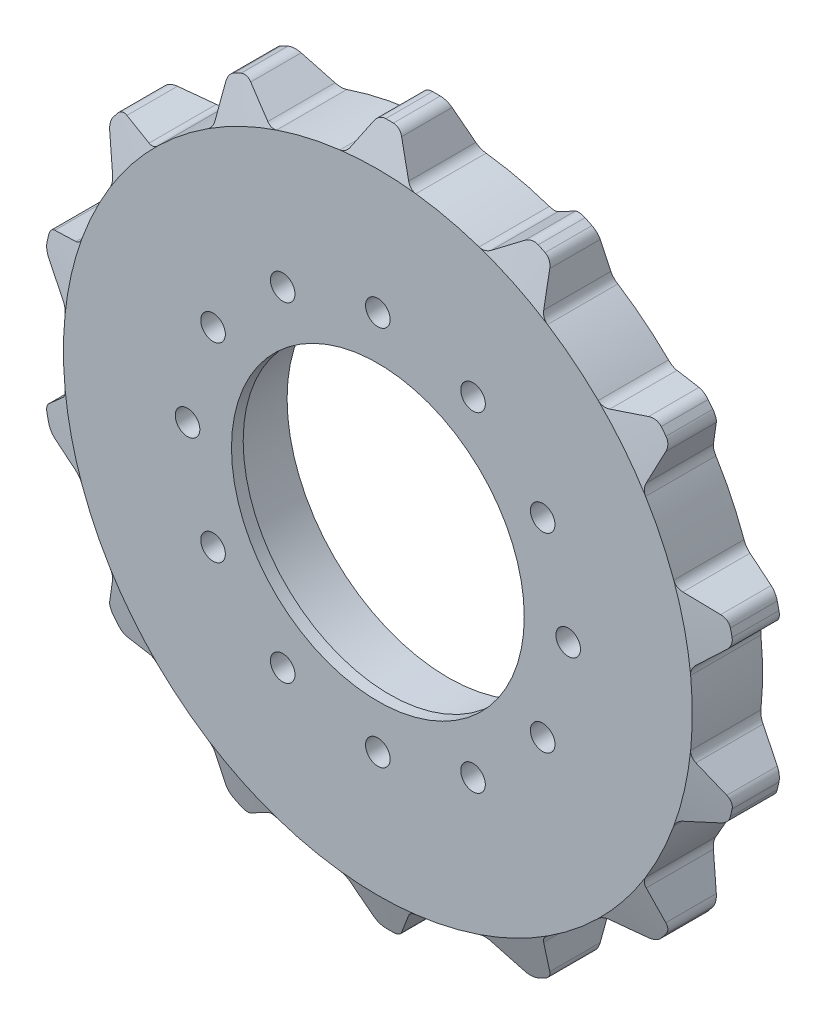
SolidWorks part; units mm, degrees
material "ABS"
ref_plane "Front" through (0, 0, 0) normal (0, 0, 1) x (1, 0, 0)
ref_plane "Top" through (0, 0, 0) normal (0, 1, 0) x (1, 0, 0)
ref_plane "Right" through (0, 0, 0) normal (1, 0, 0) x (0, 0, -1)
ref_axis "CL" through (0, 0, -5.5) along (0, 0, 1)
sketch "Sketch1" plane through (0, 0, 0) normal (0, 0, 1) x (1, 0, 0)
  circle A0 centre (0, 0) radius 53.7
  dimension "D1" = 107.4
extrude "Main Body" add sketch "Sketch1" along normal mid plane 12
sketch "Sketch2" plane through (0, 0, -6) normal (0, 0, -1) x (-1, 0, 0)
  line L0 (5.5, -53.4176) -> (1.8019, -59.8229)
  line L2 (-1.8019, -59.8229) -> (-5.5, -53.4176)
  line L3 (0, -59.85) -> (0, -53.7) construction
  circle A0 centre (0, 0) radius 53.7 construction
  arc A1 (5.5, -53.4176) -> (-5.5, -53.4176) centre (0, 0) cw
  arc A3 (1.8019, -59.8229) -> (-1.8019, -59.8229) centre (0, 0) cw
  point P10 (0, -53.7)
  circle M6 centre (0, 0) radius 53.7
  dimension "D1" = 11
  dimension "D2" = 60
  dimension "D3" = 59.85
extrude "Track Tooth" add sketch "Sketch2" against normal up to surface (12 mm away) contours L3 A3 L0 A1 | A3 L3 L2 M6 up to face at (53.7, 0, 6)
fillet "Fillet5" radius 2 4 edges at (5.5, -53.4176, 0) (-5.5, -53.4176, 0) (1.8019, -59.8229, 0) (-1.8019, -59.8229, 0)
pattern_circular "CirPattern4" count 14 over 360 about axis through (0, 0, 0) along (0, 0, 1) of "Track Tooth", "Fillet5"
sketch "Sketch3" plane through (0, 0, 0) normal (1, 0, 0) x (0, 0, -1)
  line L0 (-6, -59.85) -> (-4, -59.85)
  line L1 (-4, -59.85) -> (-6, -53.7)
  line L2 (-6, -53.7) -> (-6, -59.85)
  line L3 (-6, -50.8418) -> (-6, -53.3069) construction
  line L4 (-6, -53.4176) -> (-6, -53.7) construction
  line L5 (6, -58.8465) -> (6, -54.2923) construction
  line L8 (0, 0) -> (0, -59.85) construction
  line L9 (-6, -59.85) -> (6, -59.85) construction
  line L10 (4, -59.85) -> (6, -59.85)
  line L11 (6, -59.85) -> (6, -53.7)
  line L12 (6, -53.7) -> (4, -59.85)
  dimension "D1" = 2
  dimension "D2" = 53.7
revolve "Cut-Revolve3" cut sketch "Sketch3" angle 360 about axis through (0, 0, -5.5) along (0, 0, 1)
sketch "Sketch5" plane through (0, 0, -6) normal (0, 0, -1) x (-1, 0, 0)
  circle A0 centre (0, 0) radius 27.5
  dimension "D1" = 55
extrude "Cut-Extrude1" cut sketch "Sketch5" against normal blind 10 and the other way through all
hole_wizard "M5x0.8 Tapped Hole1" positions "Sketch7" profile "Sketch8" tap size "M5x0.8" standard "ANSI Metric" end condition up to next
sketch "Sketch7" plane through (0, 0, 6) normal (0, 0, -1) x (-1, 0, 0)
  line L0 (0, 0) -> (32.5, 0) construction
  circle A0 centre (0, 0) radius 32.5 construction
  point P0 (32.5, 0)
  dimension "D1" = 65
sketch "Sketch8" plane through (-32.5, 0, 6) normal (1, 0, 0) x (0, -1, 0)
  line L0 (0, 0) -> (0, 12.001)
  line L1 (0, 12.001) -> (2.1, 12.001)
  line L2 (2.1, 12.001) -> (2.1, 0)
  line L5 (2.1, 0) -> (0, 0)
  line L11 (0, -6.35) -> (0, 107.95) construction
  dimension "Thread Major Dia." = 4.2
  dimension "Thru Tap Drill Depth" = 12.001
pattern_circular "CirPattern9" count 12 over 360 about axis through (0, 0, 0) along (0, 0, 1) of "M5x0.8 Tapped Hole1"
sketch "Sketch10" plane through (0, 0, -6) normal (0, 0, -1) x (-1, 0, 0)
  text T0 "2mm Midline"
extrude "Midline Size Label" [suppressed] cut sketch "Sketch10" against normal blind 0.5
sketch "Sketch11" plane through (0, 0, 4) normal (0, 0, -1) x (-1, 0, 0)
  circle A0 centre (0, 0) radius 25
  dimension "D1" = 50
extrude "Cut-Extrude2" cut sketch "Sketch11" against normal up to next
equation "\"Pitch\"= 25mm"
equation "\"Num_Teeth\"= 14"
equation "\"Pitch_Diameter\"= \"Pitch\" * \"Num_Teeth\" / 3.14159"
equation "\"Track_Bend_MidLine\"= 2mm"
equation "\"D1@CirPattern4\"=\"Num_Teeth\""
